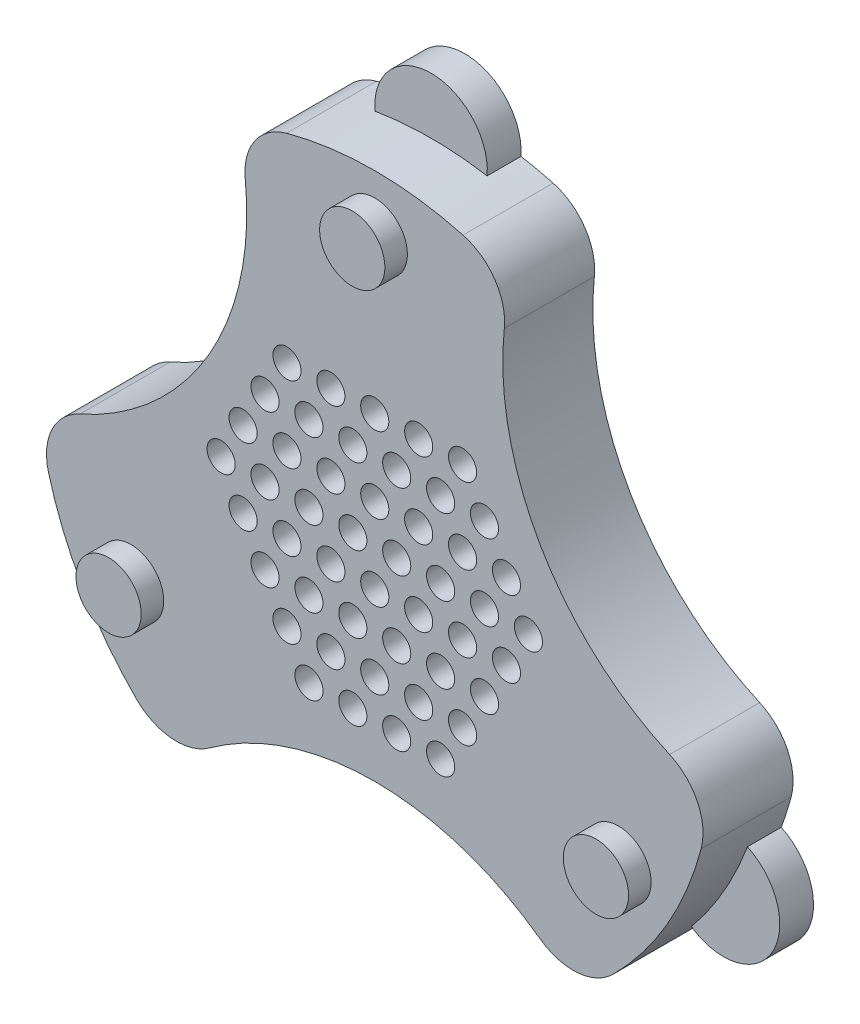
SolidWorks part; units mm, degrees
ref_plane "Спереди" through (0, 0, 0) normal (0, 0, 1) x (1, 0, 0)
ref_plane "Сверху" through (0, 0, 0) normal (0, 1, 0) x (1, 0, 0)
ref_plane "Справа" through (0, 0, 0) normal (1, 0, 0) x (0, 0, -1)
sketch "Sketch1" plane through (0, 0, 0) normal (0, 0, 1) x (1, 0, 0)
  line L0 (3.9, 6.755) -> (7.8, 0) construction
  line L2 (5.85, 10.1325) -> (11.7, 0) construction
  line L4 (7.8, 13.51) -> (15.6, 0) construction
  circle A61 centre (0, 0) radius 20
  circle A131 centre (0, 0) radius 1.25
  circle A484 centre (3.9, 0) radius 1.25
  circle A485 centre (7.8, 0) radius 1.25
  circle A486 centre (11.7, 0) radius 1.25
  circle A487 centre (15.6, 0) radius 1.25
  circle A488 centre (1.95, -3.3775) radius 1.25
  circle A489 centre (3.9, -6.755) radius 1.25
  circle A490 centre (5.85, -10.1325) radius 1.25
  circle A491 centre (7.8, -13.51) radius 1.25
  circle A492 centre (-1.95, -3.3775) radius 1.25
  circle A493 centre (-3.9, -6.755) radius 1.25
  circle A494 centre (-5.85, -10.1325) radius 1.25
  circle A495 centre (-7.8, -13.51) radius 1.25
  circle A496 centre (-3.9, 0) radius 1.25
  circle A497 centre (-7.8, 0) radius 1.25
  circle A498 centre (-11.7, 0) radius 1.25
  circle A499 centre (-15.6, 0) radius 1.25
  circle A500 centre (-1.95, 3.3775) radius 1.25
  circle A501 centre (-3.9, 6.755) radius 1.25
  circle A502 centre (-5.85, 10.1325) radius 1.25
  circle A503 centre (-7.8, 13.51) radius 1.25
  circle A504 centre (1.95, 3.3775) radius 1.25
  circle A505 centre (3.9, 6.755) radius 1.25
  circle A506 centre (5.85, 10.1325) radius 1.25
  circle A507 centre (7.8, 13.51) radius 1.25
  circle A508 centre (5.85, 3.3775) radius 1.25
  circle A509 centre (7.8, 6.755) radius 1.25
  circle A510 centre (9.75, 3.3775) radius 1.25
  circle A511 centre (11.7, 6.755) radius 1.25
  circle A512 centre (9.7491, 10.1341) radius 1.25
  circle A513 centre (13.6509, 3.3759) radius 1.25
  circle A514 centre (5.85, -3.3791) radius 1.25
  circle A515 centre (9.75, -3.3791) radius 1.25
  circle A516 centre (7.8, -6.7566) radius 1.25
  circle A517 centre (11.7, -6.7566) radius 1.25
  circle A518 centre (9.7491, -10.1356) radius 1.25
  circle A519 centre (13.6509, -3.3775) radius 1.25
  circle A520 centre (-0.0013, -6.7573) radius 1.25
  circle A521 centre (1.9487, -10.1348) radius 1.25
  circle A522 centre (-1.9513, -10.1348) radius 1.25
  circle A523 centre (-0.0013, -13.5123) radius 1.25
  circle A524 centre (-3.9032, -13.5123) radius 1.25
  circle A525 centre (3.9005, -13.5123) radius 1.25
  circle A526 centre (-5.8527, -3.3791) radius 1.25
  circle A527 centre (-7.8027, -6.7566) radius 1.25
  circle A528 centre (-9.7527, -3.3791) radius 1.25
  circle A529 centre (-11.7027, -6.7566) radius 1.25
  circle A530 centre (-13.6536, -3.3775) radius 1.25
  circle A531 centre (-9.7518, -10.1356) radius 1.25
  circle A532 centre (-5.8527, 3.3775) radius 1.25
  circle A533 centre (-9.7527, 3.3775) radius 1.25
  circle A534 centre (-7.8027, 6.755) radius 1.25
  circle A535 centre (-11.7027, 6.755) radius 1.25
  circle A536 centre (-9.7518, 10.1341) radius 1.25
  circle A537 centre (-13.6536, 3.3759) radius 1.25
  circle A538 centre (-0.0014, 6.7558) radius 1.25
  circle A539 centre (-1.9514, 10.1333) radius 1.25
  circle A540 centre (1.9486, 10.1333) radius 1.25
  circle A541 centre (-0.0014, 13.5108) radius 1.25
  circle A542 centre (3.9005, 13.5108) radius 1.25
  circle A543 centre (-3.9032, 13.5108) radius 1.25
  circle A544 centre (13.65, -1.1258) radius 2.2517 construction
  circle A545 centre (11.7009, -4.5044) radius 2.2522 construction
  circle A546 centre (9.75, -7.8834) radius 2.2522 construction
  circle A547 centre (7.7987, -11.2591) radius 2.2509 construction
  circle A548 centre (13.65, -1.1258) radius 0.65
  circle A549 centre (11.7009, -4.5044) radius 0.65
  circle A550 centre (9.75, -7.8834) radius 0.65
  circle A551 centre (7.7987, -11.2591) radius 0.65
  circle A552 centre (9.75, -1.1258) radius 0.65
  circle A553 centre (7.8009, -4.5044) radius 0.65
  circle A554 centre (5.85, -7.8834) radius 0.65
  circle A555 centre (3.8987, -11.2591) radius 0.65
  circle A556 centre (5.85, -1.1258) radius 0.65
  circle A557 centre (3.9009, -4.5044) radius 0.65
  circle A558 centre (1.95, -7.8834) radius 0.65
  circle A559 centre (-0.0013, -11.2591) radius 0.65
  circle A560 centre (1.95, -1.1258) radius 0.65
  circle A561 centre (0.0009, -4.5044) radius 0.65
  circle A562 centre (-1.95, -7.8834) radius 0.65
  circle A563 centre (-3.9013, -11.2591) radius 0.65
  circle A564 centre (-1.95, -1.1258) radius 0.65
  circle A565 centre (-3.8991, -4.5044) radius 0.65
  circle A566 centre (-5.85, -7.8834) radius 0.65
  circle A567 centre (-7.8013, -11.2591) radius 0.65
  circle A568 centre (-5.85, -1.1258) radius 0.65
  circle A569 centre (-7.7991, -4.5044) radius 0.65
  circle A570 centre (-9.75, -7.8834) radius 0.65
  circle A572 centre (-9.75, -1.1258) radius 0.65
  circle A573 centre (-11.6991, -4.5044) radius 0.65
  circle A576 centre (-13.65, -1.1258) radius 0.65
  circle A587 centre (0, 2.2517) radius 2.2517 construction
  circle A588 centre (0, 2.2517) radius 0.65
  circle A589 centre (3.9, 2.2517) radius 0.65
  circle A590 centre (7.8, 2.2517) radius 0.65
  circle A591 centre (11.7, 2.2517) radius 0.65
  circle A592 centre (15.6, 2.2517) radius 0.65
  circle A593 centre (1.9491, 5.6297) radius 2.2522 construction
  circle A594 centre (1.9491, 5.6297) radius 0.65
  circle A595 centre (5.8491, 5.6297) radius 0.65
  circle A596 centre (9.7491, 5.6297) radius 0.65
  circle A597 centre (13.6491, 5.6297) radius 0.65
  circle A598 centre (3.8991, 9.0072) radius 2.2522 construction
  circle A599 centre (3.8991, 9.0072) radius 0.65
  circle A600 centre (7.7991, 9.0072) radius 0.65
  circle A601 centre (11.6991, 9.0072) radius 0.65
  circle A602 centre (5.85, 12.3842) radius 2.2517 construction
  circle A603 centre (5.85, 12.3842) radius 0.65
  circle A604 centre (9.75, 12.3842) radius 0.65
  circle A605 centre (5.85, -14.6358) radius 0.65
  circle A606 centre (1.9509, -14.6353) radius 0.65
  circle A607 centre (-1.9491, -14.6353) radius 0.65
  circle A608 centre (-5.85, -14.6358) radius 0.65
  circle A609 centre (-15.6, 2.2517) radius 0.65
  circle A610 centre (-13.65, 5.6281) radius 0.65
  circle A611 centre (-11.7, 9.0056) radius 0.65
  circle A612 centre (-9.75, 12.3842) radius 0.65
  circle A613 centre (-5.85, 12.3842) radius 0.65
  circle A614 centre (-1.95, 12.3842) radius 0.65
  circle A615 centre (1.95, 12.3842) radius 0.65
  circle A616 centre (-7.8, 9.0056) radius 0.65
  circle A617 centre (-9.75, 5.6281) radius 0.65
  circle A618 centre (-11.7, 2.2517) radius 0.65
  circle A619 centre (-3.9, 9.0056) radius 0.65
  circle A620 centre (-5.85, 5.6281) radius 0.65
  circle A621 centre (-7.8, 2.2517) radius 0.65
  circle A622 centre (0, 9.0056) radius 0.65
  circle A623 centre (-1.95, 5.6281) radius 0.65
  circle A624 centre (-3.9, 2.2517) radius 0.65
  circle A625 centre (-15.5991, -4.5044) radius 0.65
  circle A626 centre (-13.65, -7.8834) radius 0.65
  circle A627 centre (-17.55, -7.8834) radius 0.65
  circle A628 centre (-19.5013, -11.2591) radius 0.65
  circle A629 centre (-15.6013, -11.2591) radius 0.65
  circle A630 centre (-11.7013, -11.2591) radius 0.65
  point P51 (0, 0)
  point P125 (-0.0013, -0.0008)
  point P231 (0, 0)
  dimension "D1" = 5
  dimension "D3" = 6
  dimension "D5" = 8
  dimension "D7" = 4
  dimension "D11" = 4
  dimension "D2" = 6
  dimension "D6" = 5
  dimension "D8" = 3
  dimension "D9" = 2
  dimension "D4" = 1.3
  dimension "D10" = 3
ref_plane "Plane1" through (0, 0, 10) normal (0, 0, 1) x (1, 0, 0)
sketch "Sketch2" plane through (0, 0, 10) normal (0, 0, 1) x (1, 0, 0)
  circle A63 centre (0, -2.2157) radius 1.25
  circle A64 centre (3.9, -2.2157) radius 1.25
  circle A65 centre (7.8, -2.2157) radius 1.25
  circle A92 centre (11.7, -2.2157) radius 1.25
  circle A103 centre (1.95, -5.5932) radius 1.25
  circle A107 centre (3.9, -8.9707) radius 1.25
  circle A136 centre (5.85, -12.3482) radius 1.25
  circle A138 centre (-1.95, -5.5932) radius 1.25
  circle A139 centre (-3.9, -8.9707) radius 1.25
  circle A140 centre (-5.85, -12.3482) radius 1.25
  circle A142 centre (-3.9, -2.2157) radius 1.25
  circle A143 centre (-7.8, -2.2157) radius 1.25
  circle A144 centre (-11.7, -2.2157) radius 1.25
  circle A146 centre (-1.95, 1.1618) radius 1.25
  circle A147 centre (-3.9, 4.5393) radius 1.25
  circle A148 centre (-5.85, 7.9168) radius 1.25
  circle A149 centre (-7.8, 11.2943) radius 1.25
  circle A150 centre (1.95, 1.1618) radius 1.25
  circle A151 centre (3.9, 4.5393) radius 1.25
  circle A152 centre (5.85, 7.9168) radius 1.25
  circle A153 centre (7.8, 11.2943) radius 1.25
  circle A154 centre (5.85, 1.1618) radius 1.25
  circle A155 centre (7.8, 4.5393) radius 1.25
  circle A156 centre (9.75, 1.1618) radius 1.25
  circle A157 centre (11.7, 4.5393) radius 1.25
  circle A158 centre (9.7491, 7.9183) radius 1.25
  circle A159 centre (13.6509, 1.1602) radius 1.25
  circle A160 centre (5.85, -5.5948) radius 1.25
  circle A161 centre (9.75, -5.5948) radius 1.25
  circle A162 centre (7.8, -8.9723) radius 1.25
  circle A166 centre (-0.0013, -8.9731) radius 1.25
  circle A167 centre (1.9487, -12.3506) radius 1.25
  circle A168 centre (-1.9513, -12.3506) radius 1.25
  circle A172 centre (-5.8527, -5.5948) radius 1.25
  circle A173 centre (-7.8027, -8.9723) radius 1.25
  circle A174 centre (-9.7527, -5.5948) radius 1.25
  circle A178 centre (-5.8527, 1.1618) radius 1.25
  circle A179 centre (-9.7527, 1.1618) radius 1.25
  circle A180 centre (-7.8027, 4.5393) radius 1.25
  circle A181 centre (-11.7027, 4.5393) radius 1.25
  circle A182 centre (-9.7518, 7.9183) radius 1.25
  circle A183 centre (-13.6536, 1.1602) radius 1.25
  circle A184 centre (-0.0014, 4.54) radius 1.25
  circle A185 centre (-1.9514, 7.9175) radius 1.25
  circle A186 centre (1.9486, 7.9175) radius 1.25
  circle A187 centre (-0.0014, 11.295) radius 1.25
  circle A188 centre (3.9005, 11.295) radius 1.25
  circle A189 centre (-3.9032, 11.295) radius 1.25
  circle A190 centre (0, 0) radius 16.85 construction
  circle A191 centre (0, 0) radius 19
  point P52 (0, -2.2157)
  point P126 (-0.0013, -2.2165)
  point P231 (0, -2.2157)
  dimension "D1" = 38
extrude "Boss-Extrude1" add sketch "Sketch2" along normal blind 8
sketch "Sketch3" plane through (0, 0, 18) normal (0, 0, 1) x (1, 0, 0)
  circle A0 centre (0, 0) radius 30
  circle A1 centre (0, 0) radius 17.488
extrude "Boss-Extrude2" add sketch "Sketch3" against normal blind 8
sketch "Sketch4" plane through (0, 0, 18) normal (0, 0, 1) x (1, 0, 0)
  circle A0 centre (0, 0) radius 25 construction
  circle A1 centre (0, 25) radius 2.9
  circle A2 centre (21.6506, -12.5) radius 2.9
  circle A3 centre (-21.6506, -12.5) radius 2.9
  point P11 (0, 0)
  dimension "D1" = 3
extrude "Boss-Extrude3" add sketch "Sketch4" along normal blind 2
sketch "Sketch6" plane through (0, 0, 10) normal (0, 0, -1) x (-1, 0, 0)
  circle A0 centre (0, 30) radius 5
  circle A1 centre (0, 0) radius 30 construction
  circle A2 centre (25.9808, -15) radius 5
  circle A3 centre (-25.9808, -15) radius 5
  circle A4 centre (0, 0) radius 30 construction
  point P5 (0, 30)
  point P10 (0, 0)
  point P12 (1.0017, 29.9833)
  point P13 (-1.4493, 29.965)
  point P14 (0, 0)
  point P15 (0, 30)
  point P16 (-0.8991, 29.9865)
  point P17 (0, 30)
  dimension "D1" = 3
extrude "Boss-Extrude4" add sketch "Sketch6" against normal blind 3
sketch "Sketch5" plane through (0, 0, 10) normal (0, 0, -1) x (-1, 0, 0)
  circle A0 centre (0, 25) radius 3
  circle A1 centre (21.6506, -12.5) radius 3
  circle A2 centre (-21.6506, -12.5) radius 3
extrude "Cut-Extrude1" cut sketch "Sketch5" against normal blind 3
sketch "Sketch7" plane through (0, 0, 10) normal (0, 0, -1) x (-1, 0, 0)
  line L0 (-36.3731, 21) -> (0, 0)
  line L8 (36.3731, 21) -> (0, 0)
  line L9 (0, -42) -> (0, 0)
  circle A1 centre (36.3731, 21) radius 25
  circle A3 centre (0, -42) radius 25
  circle A9 centre (0, 0) radius 42 construction
  circle A10 centre (-36.3731, 21) radius 25
  point P10 (0, 0)
  point P11 (0, 0)
  point P24 (0, 0)
  dimension "D1" = 3
extrude "Cut-Extrude2" cut sketch "Sketch7" against normal blind 8
fillet "Fillet2" radius 5 6 edges at (17.629, -24.2738, 14) (-17.629, -24.2738, 14) (-29.8362, -3.1303, 14) (-12.2072, 27.4041, 14) (12.2072, 27.4041, 14) (29.8362, -3.1303, 14)
